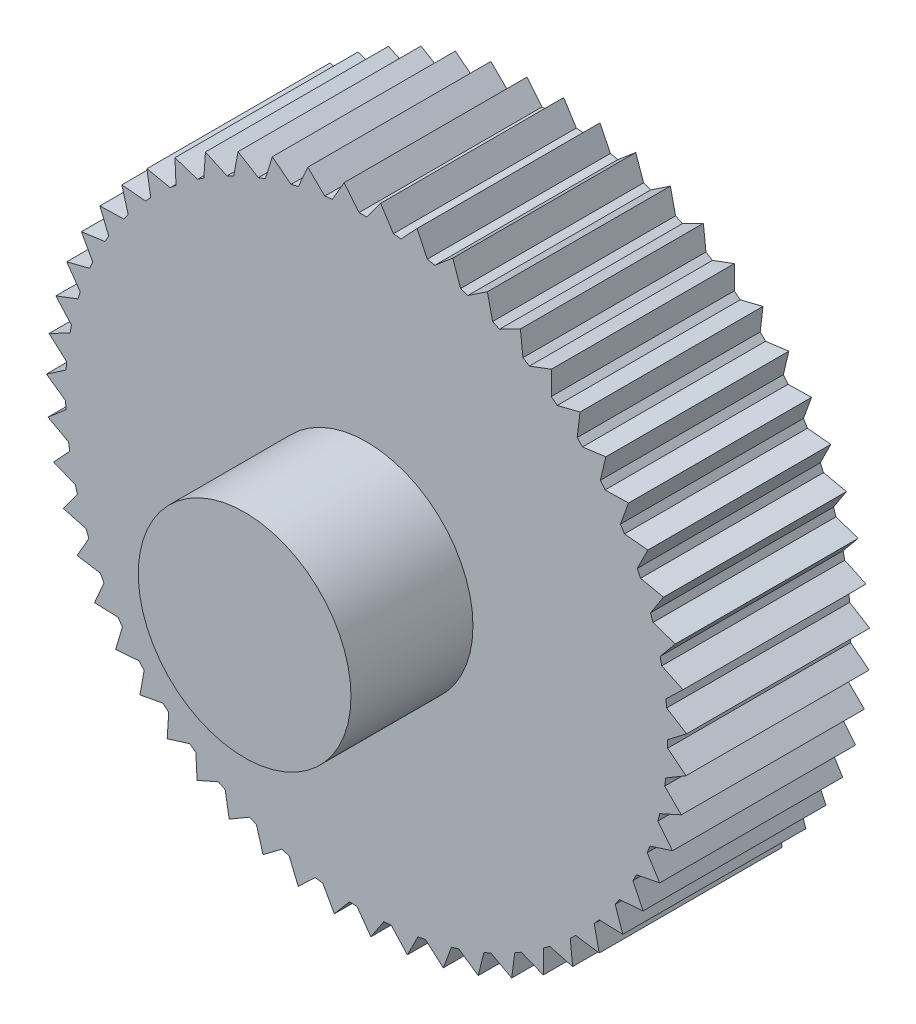
SolidWorks part; units mm, degrees
ref_plane "Front Plane" through (0, 0, 0) normal (0, 0, 1) x (1, 0, 0)
ref_plane "Top Plane" through (0, 0, 0) normal (0, 1, 0) x (1, 0, 0)
ref_plane "Right Plane" through (0, 0, 0) normal (1, 0, 0) x (0, 0, -1)
sketch "Sketch1" plane through (0, 0, 0) normal (0, 0, 1) x (1, 0, 0)
  line L0 (0, 24.68) -> (1.1502, 26.2243)
  line L1 (1.1502, 26.2243) -> (2.1923, 24.5824)
  line L2 (2.8133, 24.5191) -> (4.132, 25.9222)
  line L3 (4.132, 25.9222) -> (4.9802, 24.1723)
  line L4 (5.5899, 24.0386) -> (7.06, 25.2822)
  line L5 (7.06, 25.2822) -> (7.7032, 23.447)
  line L6 (8.2937, 23.2447) -> (9.8959, 24.3127)
  line L7 (9.8959, 24.3127) -> (10.3257, 22.4161)
  line L8 (10.8893, 22.1478) -> (12.6029, 23.0261)
  line L9 (12.6029, 23.0261) -> (12.8137, 21.093)
  line L10 (13.343, 20.7621) -> (15.1455, 21.4394)
  line L11 (15.1455, 21.4394) -> (15.1346, 19.4948)
  line L12 (15.6227, 19.1058) -> (17.4907, 19.5732)
  line L13 (17.4907, 19.5732) -> (17.2581, 17.6425)
  line L14 (17.6988, 17.2004) -> (19.6079, 17.4519)
  line L15 (19.6079, 17.4519) -> (19.1567, 15.5603)
  line L16 (19.5441, 15.0708) -> (21.4694, 15.103)
  line L17 (21.4694, 15.103) -> (20.8056, 13.2751)
  line L18 (21.1347, 12.7447) -> (23.0511, 12.5572)
  line L19 (23.0511, 12.5572) -> (22.1832, 10.8169)
  line L20 (22.4497, 10.2524) -> (24.3322, 9.8477)
  line L21 (24.3322, 9.8477) -> (23.2717, 8.2177)
  line L22 (23.4721, 7.6265) -> (25.2962, 7.0099)
  line L23 (25.2962, 7.0099) -> (24.0567, 5.5114)
  line L24 (24.1884, 4.9012) -> (25.9304, 4.0806)
  line L25 (25.9304, 4.0806) -> (24.5282, 2.7332)
  line L26 (24.5895, 2.112) -> (26.2265, 1.0982)
  line L27 (26.2265, 1.0982) -> (24.6799, -0.0806)
  line L28 (24.6699, -0.7048) -> (26.1807, -1.8986)
  line L29 (26.1807, -1.8986) -> (24.5098, -2.8934)
  line L30 (24.4288, -3.5123) -> (25.7937, -4.8706)
  line L31 (25.7937, -4.8706) -> (24.0202, -5.6684)
  line L32 (23.8692, -6.2741) -> (25.0703, -7.7791)
  line L33 (25.0703, -7.7791) -> (23.2175, -8.3696)
  line L34 (22.9984, -8.9541) -> (24.0202, -10.5862)
  line L35 (24.0202, -10.5862) -> (22.1121, -10.9616)
  line L36 (21.8278, -11.5173) -> (22.6569, -13.2553)
  line L37 (22.6569, -13.2553) -> (20.7184, -13.4108)
  line L38 (20.3726, -13.9305) -> (20.9982, -15.7515)
  line L39 (20.9982, -15.7515) -> (19.0547, -15.6851)
  line L40 (18.6519, -16.162) -> (19.0658, -18.0425)
  line L41 (19.0658, -18.0425) -> (17.1425, -17.7549)
  line L42 (16.688, -18.1828) -> (16.8848, -20.0982)
  line L43 (16.8848, -20.0982) -> (15.0069, -19.5933)
  line L44 (14.5065, -19.9665) -> (14.4837, -21.8919)
  line L45 (14.4837, -21.8919) -> (12.6756, -21.1762)
  line L46 (12.136, -21.49) -> (11.8938, -23.4003)
  line L47 (11.8938, -23.4003) -> (10.1791, -22.4831)
  line L48 (9.6072, -22.7333) -> (9.1489, -24.6035)
  line L49 (9.1489, -24.6035) -> (7.5498, -23.4969)
  line L50 (6.9532, -23.6803) -> (6.2847, -25.486)
  line L51 (6.2847, -25.486) -> (4.8222, -24.2043)
  line L52 (4.2085, -24.3185) -> (3.3385, -26.0363)
  line L53 (3.3385, -26.0363) -> (2.0317, -24.5962)
  line L54 (1.409, -24.6397) -> (0.3488, -26.2472)
  line L55 (0.3488, -26.2472) -> (-0.7853, -24.6675)
  line L56 (-1.409, -24.6397) -> (-2.6454, -26.1158)
  line L57 (-2.6454, -26.1158) -> (-3.5921, -24.4172)
  line L58 (-4.2085, -24.3185) -> (-5.6051, -25.6441)
  line L59 (-5.6051, -25.6441) -> (-6.352, -23.8486)
  line L60 (-6.9532, -23.6803) -> (-8.4918, -24.838)
  line L61 (-8.4918, -24.838) -> (-9.0292, -22.969)
  line L62 (-9.6072, -22.7333) -> (-11.2678, -23.7081)
  line L63 (-11.2678, -23.7081) -> (-11.5886, -21.7901)
  line L64 (-12.136, -21.49) -> (-13.8968, -22.2691)
  line L65 (-13.8968, -22.2691) -> (-13.9969, -20.327)
  line L66 (-14.5065, -19.9665) -> (-16.3447, -20.5398)
  line L67 (-16.3447, -20.5398) -> (-16.2228, -18.599)
  line L68 (-16.688, -18.1828) -> (-18.5796, -18.5428)
  line L69 (-18.5796, -18.5428) -> (-18.2372, -16.6285)
  line L70 (-18.6519, -16.162) -> (-20.5722, -16.304)
  line L71 (-20.5722, -16.304) -> (-20.0138, -14.4412)
  line L72 (-20.3726, -13.9305) -> (-22.2966, -13.8527)
  line L73 (-22.2966, -13.8527) -> (-21.5295, -12.0657)
  line L74 (-21.8278, -11.5173) -> (-23.7304, -11.2208)
  line L75 (-23.7304, -11.2208) -> (-22.7646, -9.5329)
  line L76 (-22.9984, -8.9541) -> (-24.8547, -8.4426)
  line L77 (-24.8547, -8.4426) -> (-23.7029, -6.8758)
  line L78 (-23.8692, -6.2741) -> (-25.6551, -5.5543)
  line L79 (-25.6551, -5.5543) -> (-24.3322, -4.129)
  line L80 (-24.4288, -3.5123) -> (-26.121, -2.5936)
  line L81 (-26.121, -2.5936) -> (-24.6442, -1.3285)
  line L82 (-24.6699, -0.7048) -> (-26.2464, 0.4008)
  line L83 (-26.2464, 0.4008) -> (-24.635, 1.4894)
  line L84 (-24.5895, 2.112) -> (-26.0296, 3.3901)
  line L85 (-26.0296, 3.3901) -> (-24.3047, 4.2879)
  line L86 (-24.1884, 4.9012) -> (-25.4735, 6.3351)
  line L87 (-25.4735, 6.3351) -> (-23.6574, 7.0305)
  line L88 (-23.4721, 7.6265) -> (-24.5853, 9.1976)
  line L89 (-24.5853, 9.1976) -> (-22.7018, 9.6814)
  line L90 (-22.4497, 10.2524) -> (-23.3766, 11.9402)
  line L91 (-23.3766, 11.9402) -> (-21.4503, 12.2061)
  line L92 (-21.1347, 12.7447) -> (-21.8632, 14.5271)
  line L93 (-21.8632, 14.5271) -> (-19.919, 14.5717)
  line L94 (-19.5441, 15.0708) -> (-20.0647, 16.9246)
  line L95 (-20.0647, 16.9246) -> (-18.1282, 16.7473)
  line L96 (-17.6988, 17.2004) -> (-18.0047, 19.1015)
  line L97 (-18.0047, 19.1015) -> (-16.1009, 18.7046)
  line L98 (-15.6227, 19.1058) -> (-15.7099, 21.0294)
  line L99 (-15.7099, 21.0294) -> (-13.8638, 20.418)
  line L100 (-13.343, 20.7621) -> (-13.2103, 22.6831)
  line L101 (-13.2103, 22.6831) -> (-11.446, 21.8653)
  line L102 (-10.8893, 22.1478) -> (-10.5385, 24.0411)
  line L103 (-10.5385, 24.0411) -> (-8.8789, 23.0275)
  line L104 (-8.2937, 23.2447) -> (-7.7294, 25.0857)
  line L105 (-7.7294, 25.0857) -> (-6.1961, 23.8896)
  line L106 (-5.5899, 24.0386) -> (-4.8194, 25.8033)
  line L107 (-4.8194, 25.8033) -> (-3.4325, 24.4401)
  line L108 (-2.8133, 24.5191) -> (-1.8467, 26.1844)
  line L109 (-1.8467, 26.1844) -> (-0.6242, 24.6721)
  arc A0 (-10.8893, 22.1478) -> (-11.446, 21.8653) centre (0, 0) ccw
  arc A1 (-8.2937, 23.2447) -> (-8.8789, 23.0275) centre (0, 0) ccw
  arc A2 (-5.5899, 24.0386) -> (-6.1961, 23.8896) centre (0, 0) ccw
  arc A3 (-2.8133, 24.5191) -> (-3.4325, 24.4401) centre (0, 0) ccw
  arc A4 (0, 24.68) -> (-0.6242, 24.6721) centre (0, 0) ccw
  arc A5 (2.8133, 24.5191) -> (2.1923, 24.5824) centre (0, 0) ccw
  arc A6 (5.5899, 24.0386) -> (4.9802, 24.1723) centre (0, 0) ccw
  arc A7 (8.2937, 23.2447) -> (7.7032, 23.447) centre (0, 0) ccw
  arc A8 (-24.1884, 4.9012) -> (-24.3047, 4.2879) centre (0, 0) ccw
  arc A9 (-23.4721, 7.6265) -> (-23.6574, 7.0305) centre (0, 0) ccw
  arc A10 (-22.4497, 10.2524) -> (-22.7018, 9.6814) centre (0, 0) ccw
  arc A11 (-21.1347, 12.7447) -> (-21.4503, 12.2061) centre (0, 0) ccw
  arc A12 (-17.6988, 17.2004) -> (-18.1282, 16.7473) centre (0, 0) ccw
  arc A13 (-19.5441, 15.0708) -> (-19.919, 14.5717) centre (0, 0) ccw
  arc A14 (-15.6227, 19.1058) -> (-16.1009, 18.7046) centre (0, 0) ccw
  arc A15 (-13.343, 20.7621) -> (-13.8638, 20.418) centre (0, 0) ccw
  arc A16 (-14.5065, -19.9665) -> (-13.9969, -20.327) centre (0, 0) ccw
  arc A17 (-12.136, -21.49) -> (-11.5886, -21.7901) centre (0, 0) ccw
  arc A18 (-9.6072, -22.7333) -> (-9.0292, -22.969) centre (0, 0) ccw
  arc A19 (-6.9532, -23.6803) -> (-6.352, -23.8486) centre (0, 0) ccw
  arc A20 (-4.2085, -24.3185) -> (-3.5921, -24.4172) centre (0, 0) ccw
  arc A21 (-1.409, -24.6397) -> (-0.7853, -24.6675) centre (0, 0) ccw
  arc A22 (1.409, -24.6397) -> (2.0317, -24.5962) centre (0, 0) ccw
  arc A23 (4.2085, -24.3185) -> (4.8222, -24.2043) centre (0, 0) ccw
  arc A24 (6.9532, -23.6803) -> (7.5498, -23.4969) centre (0, 0) ccw
  arc A25 (9.6072, -22.7333) -> (10.1791, -22.4831) centre (0, 0) ccw
  arc A26 (12.136, -21.49) -> (12.6756, -21.1762) centre (0, 0) ccw
  arc A27 (14.5065, -19.9665) -> (15.0069, -19.5933) centre (0, 0) ccw
  arc A28 (16.688, -18.1828) -> (17.1425, -17.7549) centre (0, 0) ccw
  arc A29 (18.6519, -16.162) -> (19.0547, -15.6851) centre (0, 0) ccw
  arc A30 (20.3726, -13.9305) -> (20.7184, -13.4108) centre (0, 0) ccw
  arc A31 (21.1347, 12.7447) -> (20.8056, 13.2751) centre (0, 0) ccw
  arc A32 (22.4497, 10.2524) -> (22.1832, 10.8169) centre (0, 0) ccw
  arc A33 (23.4721, 7.6265) -> (23.2717, 8.2177) centre (0, 0) ccw
  arc A34 (24.1884, 4.9012) -> (24.0567, 5.5114) centre (0, 0) ccw
  arc A35 (24.5895, 2.112) -> (24.5282, 2.7332) centre (0, 0) ccw
  arc A36 (24.6699, -0.7048) -> (24.6799, -0.0806) centre (0, 0) ccw
  arc A37 (24.4288, -3.5123) -> (24.5098, -2.8934) centre (0, 0) ccw
  arc A38 (21.8278, -11.5173) -> (22.1121, -10.9616) centre (0, 0) ccw
  arc A39 (22.9984, -8.9541) -> (23.2175, -8.3696) centre (0, 0) ccw
  arc A40 (23.8692, -6.2741) -> (24.0202, -5.6684) centre (0, 0) ccw
  arc A41 (10.8893, 22.1478) -> (10.3257, 22.4161) centre (0, 0) ccw
  arc A42 (13.343, 20.7621) -> (12.8137, 21.093) centre (0, 0) ccw
  arc A43 (15.6227, 19.1058) -> (15.1346, 19.4948) centre (0, 0) ccw
  arc A44 (17.6988, 17.2004) -> (17.2581, 17.6425) centre (0, 0) ccw
  arc A45 (19.5441, 15.0708) -> (19.1567, 15.5603) centre (0, 0) ccw
  arc A46 (-16.688, -18.1828) -> (-16.2228, -18.599) centre (0, 0) ccw
  arc A47 (-18.6519, -16.162) -> (-18.2372, -16.6285) centre (0, 0) ccw
  arc A48 (-20.3726, -13.9305) -> (-20.0138, -14.4412) centre (0, 0) ccw
  arc A49 (-21.8278, -11.5173) -> (-21.5295, -12.0657) centre (0, 0) ccw
  arc A50 (-22.9984, -8.9541) -> (-22.7646, -9.5329) centre (0, 0) ccw
  arc A51 (-23.8692, -6.2741) -> (-23.7029, -6.8758) centre (0, 0) ccw
  arc A52 (-24.4288, -3.5123) -> (-24.3322, -4.129) centre (0, 0) ccw
  arc A53 (-24.6699, -0.7048) -> (-24.6442, -1.3285) centre (0, 0) ccw
  arc A54 (-24.5895, 2.112) -> (-24.635, 1.4894) centre (0, 0) ccw
  circle A55 centre (0, 0) radius 8.7172
  point P171 (0, 0)
extrude "Boss-Extrude1" add sketch "Sketch1" along normal blind 15
sketch "Sketch2" plane through (0, 0, 15) normal (0, 0, 1) x (1, 0, 0)
  circle A0 centre (0, 0) radius 8.7172
extrude "Boss-Extrude2" add sketch "Sketch2" along normal blind 10 separate body
fillet "Fillet1" radius 1 1 edges at (8.7172, 0, 0)
sketch "Sketch3" plane through (0, 0, 15) normal (0, 0, -1) x (-1, 0, 0)
  circle A0 centre (0, 0) radius 8.7172
extrude "Boss-Extrude3" add sketch "Sketch3" along normal blind 5
